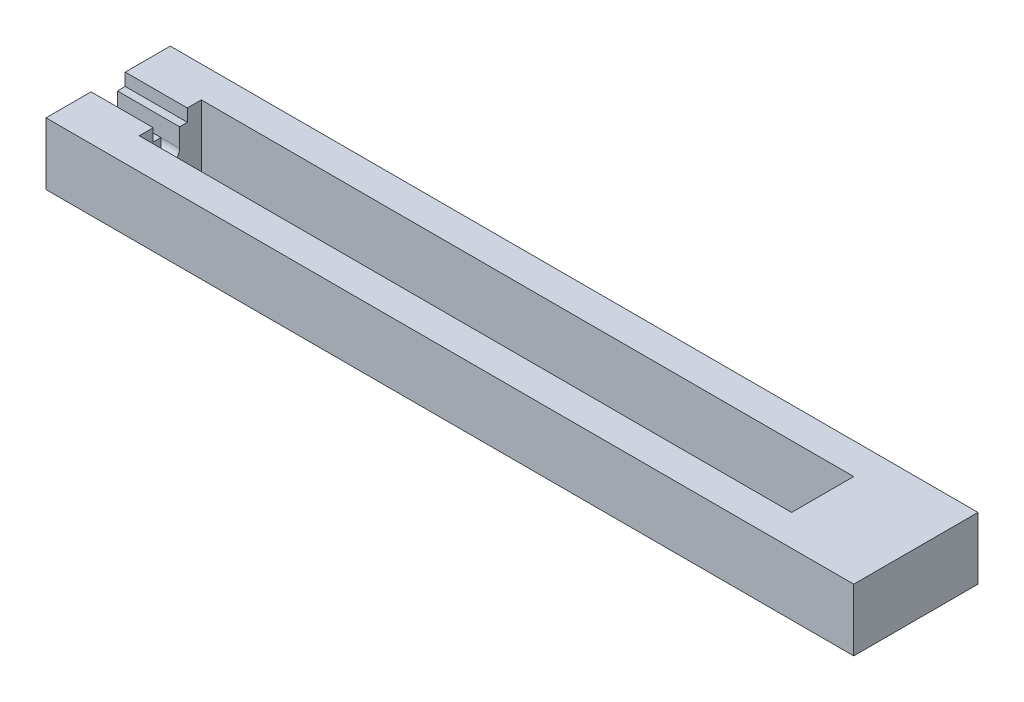
SolidWorks part; units mm, degrees
ref_plane "Front Plane" through (0, 0, 0) normal (0, 0, 1) x (1, 0, 0)
ref_plane "Top Plane" through (0, 0, 0) normal (0, 1, 0) x (1, 0, 0)
ref_plane "Right Plane" through (0, 0, 0) normal (1, 0, 0) x (0, 0, -1)
sketch "Sketch1" plane through (0, 0, 0) normal (0, 1, 0) x (1, 0, 0)
  line L1 (-6.5, -1) -> (6.5, -1)
  line L2 (-6.5, -1) -> (-6.5, 1)
  line L3 (-6.5, 1) -> (6.5, 1)
  line L4 (6.5, -1) -> (6.5, 1)
  line L5 (-6.5, -1) -> (6.5, 1) construction
  line L6 (-6.5, 1) -> (6.5, -1) construction
  line L7 (-5.5, 0.5) -> (5, 0.5)
  line L8 (-5.5, 0.5) -> (-5.5, -0.5)
  line L9 (-5.5, -0.5) -> (5, -0.5)
  line L10 (5, 0.5) -> (5, -0.5)
  point P0 (0, 0)
  point P6 (0, 0)
  dimension "D1" = 2
  dimension "D2" = 13
  dimension "D3" = 1
  dimension "D4" = 1.5
  dimension "D5" = 1
extrude "Boss-Extrude1" add sketch "Sketch1" along normal blind 1
sketch "Sketch2" plane through (-6.5, 0, 0) normal (-1, 0, 0) x (0, 0, 1)
  line L0 (0.15, 0.8) -> (0.275, 0.8)
  line L1 (-1, 1) -> (1, 1) construction
  line L3 (0.15, 0.5) -> (0.15, 0.8)
  line L4 (0.15, 1) -> (-0.15, 1)
  line L5 (1, 1) -> (1, 0) construction
  line L6 (-0.15, 0.5) -> (-0.15, 0.8)
  line L7 (-1, 0) -> (1, 0) construction
  line L9 (-0.275, 0.8) -> (-0.15, 0.8)
  line L10 (-0.275, 0.8) -> (-0.275, 1)
  line L11 (-0.275, 1) -> (0.275, 1)
  line L12 (0.275, 0.8) -> (0.275, 1)
  arc A0 (-0.15, 0.5) -> (0.15, 0.5) centre (0, 0.5) ccw
  point P12 (0, 0.9)
  line M3 (1, 1) -> (-1, 1)
  dimension "D1" = 0.55
  dimension "D2" = 0.2
  dimension "D3" = 1
  dimension "D4" = 0
  dimension "D5" = 0.5
extrude "Cut-Extrude2" cut sketch "Sketch2" against normal blind 1 contours L6 A0 L3 L0 L12 L10 L9 M3
ref_plane "Plane1" through (0, 0.5, 0) normal (0, -1, 0) x (-1, 0, 0)
